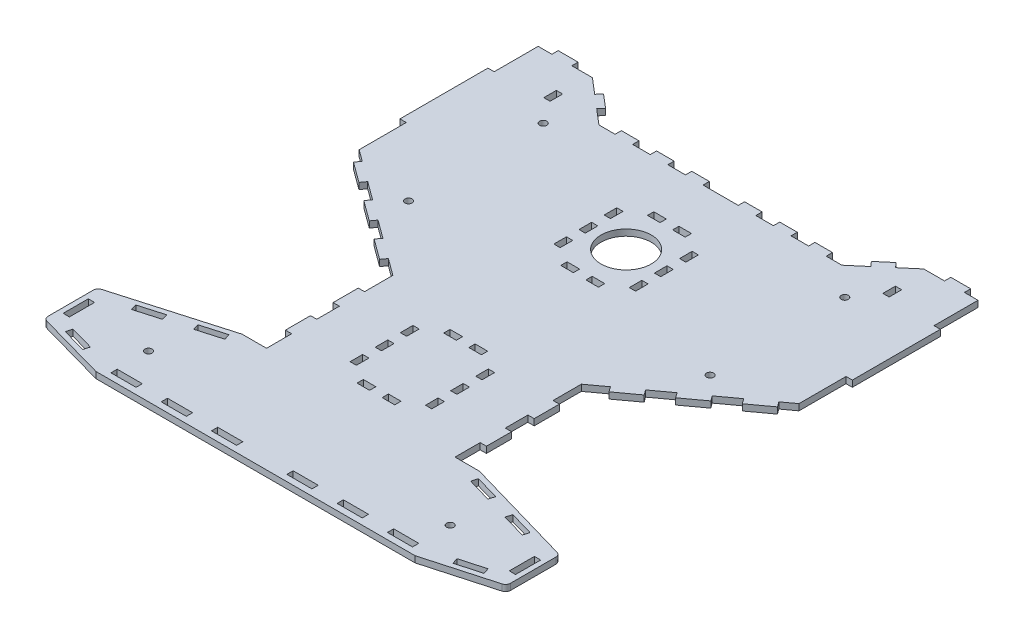
SolidWorks part; units mm, degrees
material "Beech"
ref_plane "Front" through (0, 0, 0) normal (0, 0, 1) x (1, 0, 0)
ref_plane "Top" through (0, 0, 0) normal (0, 1, 0) x (1, 0, 0)
ref_plane "Right" through (0, 0, 0) normal (1, 0, 0) x (0, 0, -1)
sketch "Sketch1" plane through (0, 0, 0) normal (0, 1, 0) x (1, 0, 0)
  line L0 (47.4037, 85) -> (-47.4037, 85) construction
  line L1 (-90, -100) -> (90, -100) construction
  line L2 (-90, -100) -> (-90, 100) construction
  line L3 (-90, 100) -> (90, 100) construction
  line L4 (90, -100) -> (90, 100) construction
  line L5 (-90, -100) -> (90, 100) construction
  line L6 (-90, 100) -> (90, -100) construction
  line L7 (-47.4037, 85) -> (-64.159, 99.2831) construction
  line L10 (-87.5, 23.171) -> (-40, -11.5806) construction
  line L14 (-90, -100) -> (90, -100) construction
  line L15 (0, 23.9102) -> (0, -23.5083) construction
  line L16 (90, -75) -> (90, -100) construction
  line L17 (40, -60.5806) -> (90, -75) construction
  line L18 (40, -11.5806) -> (40, -60.5806) construction
  line L22 (47.4037, 85) -> (64.159, 99.2831) construction
  line L23 (2.5, 63.5) -> (7.5, 63.5)
  line L30 (-15, 27.75) -> (15, 27.75) construction
  line L31 (-15, 27.75) -> (-15, 62.25) construction
  line L32 (-15, 62.25) -> (15, 62.25) construction
  line L33 (15, 27.75) -> (15, 62.25) construction
  line L34 (-15, 27.75) -> (15, 62.25) construction
  line L35 (-15, 62.25) -> (15, 27.75) construction
  line L36 (-7.5, 61) -> (-2.5, 61)
  line L37 (-7.5, 61) -> (-7.5, 63.5)
  line L38 (-7.5, 63.5) -> (-2.5, 63.5)
  line L39 (-2.5, 61) -> (-2.5, 63.5)
  line L40 (-7.5, 61) -> (-2.5, 63.5) construction
  line L41 (-7.5, 63.5) -> (-2.5, 61) construction
  line L42 (7.5, 61) -> (7.5, 63.5)
  line L43 (2.5, 61) -> (7.5, 61)
  line L44 (2.5, 61) -> (2.5, 63.5)
  line L53 (5.5621, 45) -> (-5.5621, 45) construction
  line L62 (-7.5, 26.5) -> (-2.5, 26.5)
  line L63 (-2.5, 29) -> (-2.5, 26.5)
  line L64 (-7.5, 29) -> (-2.5, 29)
  line L65 (-7.5, 29) -> (-7.5, 26.5)
  line L66 (2.5, 29) -> (2.5, 26.5)
  line L67 (2.5, 29) -> (7.5, 29)
  line L68 (7.5, 29) -> (7.5, 26.5)
  line L69 (2.5, 26.5) -> (7.5, 26.5)
  line L70 (-16.25, 47.5) -> (-16.25, 42.5)
  line L71 (-13.75, 57.5) -> (-16.25, 57.5)
  line L72 (-13.75, 57.5) -> (-13.75, 52.5)
  line L73 (-13.75, 52.5) -> (-16.25, 52.5)
  line L74 (-16.25, 57.5) -> (-16.25, 52.5)
  line L75 (-13.75, 57.5) -> (-16.25, 52.5) construction
  line L76 (-13.75, 52.5) -> (-16.25, 57.5) construction
  line L77 (-13.75, 42.5) -> (-16.25, 42.5)
  line L78 (-13.75, 47.5) -> (-13.75, 42.5)
  line L79 (-13.75, 47.5) -> (-16.25, 47.5)
  line L80 (-16.25, 37.5) -> (-16.25, 32.5)
  line L81 (-13.75, 32.5) -> (-16.25, 32.5)
  line L82 (-13.75, 37.5) -> (-13.75, 32.5)
  line L83 (-13.75, 37.5) -> (-16.25, 37.5)
  line L88 (13.75, 52.5) -> (16.25, 52.5)
  line L89 (16.25, 57.5) -> (16.25, 52.5)
  line L90 (13.75, 57.5) -> (16.25, 57.5)
  line L91 (13.75, 57.5) -> (13.75, 52.5)
  line L92 (13.75, 47.5) -> (16.25, 47.5)
  line L93 (13.75, 47.5) -> (13.75, 42.5)
  line L94 (13.75, 42.5) -> (16.25, 42.5)
  line L95 (16.25, 47.5) -> (16.25, 42.5)
  line L96 (13.75, 37.5) -> (16.25, 37.5)
  line L97 (13.75, 37.5) -> (13.75, 32.5)
  line L98 (13.75, 32.5) -> (16.25, 32.5)
  line L99 (16.25, 37.5) -> (16.25, 32.5)
  line L104 (-87.5, 80) -> (-90, 80)
  line L105 (87.5, 80) -> (90, 80)
  line L106 (87.5, 80) -> (87.5, 45)
  line L107 (87.5, 45) -> (90, 45)
  line L108 (90, 80) -> (90, 45)
  line L109 (87.5, 80) -> (90, 45) construction
  line L110 (87.5, 45) -> (90, 80) construction
  line L111 (-87.5, 80) -> (-87.5, 45)
  line L112 (-87.5, 45) -> (-90, 45)
  line L113 (-90, 80) -> (-90, 45)
  line L114 (-66.1052, 100) -> (-87.5, 100) construction
  line L115 (-87.5, 100) -> (-87.5, 23.171)
  line L116 (-87.5, 100.2764) -> (-87.5, 23.4474)
  line L117 (66.1052, 100) -> (87.5, 100) construction
  line L118 (87.5, 100) -> (87.5, 23.171)
  line L119 (-13.75, -28.5806) -> (-16.25, -28.5806)
  line L122 (-13.75, -23.5806) -> (-16.25, -28.5806) construction
  line L123 (-7.5, -20.0806) -> (-2.5, -17.5806) construction
  line L125 (-15, -18.8306) -> (15, -53.3306) construction
  line L129 (-13.75, -23.5806) -> (-13.75, -28.5806)
  line L130 (-13.75, -23.5806) -> (-16.25, -23.5806)
  line L134 (-15, -53.3306) -> (15, -18.8306) construction
  line L135 (-15, -53.3306) -> (-15, -18.8306) construction
  line L142 (-7.5, -17.5806) -> (-2.5, -20.0806) construction
  line L152 (-16.25, -23.5806) -> (-16.25, -28.5806)
  line L160 (-7.5, -20.0806) -> (-7.5, -17.5806)
  line L163 (15, -53.3306) -> (15, -18.8306) construction
  line L168 (-87.5, 97.5) -> (-62.0673, 97.5) construction
  line L174 (-15, -18.8306) -> (15, -18.8306) construction
  line L180 (-7.5, -20.0806) -> (-2.5, -20.0806)
  line L183 (-15, -53.3306) -> (15, -53.3306) construction
  line L184 (-2.5, -20.0806) -> (-2.5, -17.5806)
  line L185 (-7.5, -17.5806) -> (-2.5, -17.5806)
  line L193 (5.7531, -36.0806) -> (-5.3943, -36.0806) construction
  line L197 (-65.921, 97.5) -> (-48.3247, 82.5) construction
  line L199 (-13.75, -28.5806) -> (-16.25, -23.5806) construction
  line L200 (2.5, -20.0806) -> (2.5, -17.5806)
  line L201 (2.5, -17.5806) -> (7.5, -17.5806)
  line L202 (7.5, -20.0806) -> (7.5, -17.5806)
  line L203 (2.5, -20.0806) -> (7.5, -20.0806)
  line L212 (-13.75, -38.5806) -> (-16.25, -38.5806)
  line L213 (-16.25, -33.5806) -> (-16.25, -38.5806)
  line L214 (-13.75, -33.5806) -> (-16.25, -33.5806)
  line L215 (-13.75, -33.5806) -> (-13.75, -38.5806)
  line L216 (-13.75, -48.5806) -> (-16.25, -48.5806)
  line L217 (-16.25, -43.5806) -> (-16.25, -48.5806)
  line L218 (-13.75, -43.5806) -> (-16.25, -43.5806)
  line L219 (-13.75, -43.5806) -> (-13.75, -48.5806)
  line L232 (2.5, -52.0806) -> (7.5, -52.0806)
  line L233 (7.5, -52.0806) -> (7.5, -54.5806)
  line L234 (2.5, -54.5806) -> (7.5, -54.5806)
  line L235 (2.5, -52.0806) -> (2.5, -54.5806)
  line L236 (-7.5, -52.0806) -> (-2.5, -52.0806)
  line L237 (-2.5, -52.0806) -> (-2.5, -54.5806)
  line L238 (-7.5, -54.5806) -> (-2.5, -54.5806)
  line L239 (-7.5, -52.0806) -> (-7.5, -54.5806)
  line L240 (13.75, -23.5806) -> (13.75, -28.5806)
  line L241 (13.75, -23.5806) -> (16.25, -23.5806)
  line L242 (16.25, -23.5806) -> (16.25, -28.5806)
  line L243 (13.75, -28.5806) -> (16.25, -28.5806)
  line L244 (13.75, -33.5806) -> (13.75, -38.5806)
  line L245 (13.75, -33.5806) -> (16.25, -33.5806)
  line L246 (16.25, -33.5806) -> (16.25, -38.5806)
  line L247 (13.75, -38.5806) -> (16.25, -38.5806)
  line L248 (13.75, -43.5806) -> (13.75, -48.5806)
  line L249 (13.75, -43.5806) -> (16.25, -43.5806)
  line L250 (16.25, -43.5806) -> (16.25, -48.5806)
  line L251 (13.75, -48.5806) -> (16.25, -48.5806)
  line L256 (-16.25, 27.5) -> (-16.25, 22.5) [skipped]
  line L257 (-13.75, 22.5) -> (-16.25, 22.5) [skipped]
  line L258 (-13.75, 27.5) -> (-13.75, 22.5) [skipped]
  line L259 (-13.75, 27.5) -> (-16.25, 27.5) [skipped]
  line L260 (22.5, 63.5) -> (27.5, 63.5) [skipped]
  line L261 (27.5, 61) -> (27.5, 63.5) [skipped]
  line L262 (22.5, 61) -> (27.5, 61) [skipped]
  line L263 (22.5, 61) -> (22.5, 63.5) [skipped]
  line L264 (12.5, 63.5) -> (17.5, 63.5) [skipped]
  line L265 (17.5, 61) -> (17.5, 63.5) [skipped]
  line L266 (12.5, 61) -> (17.5, 61) [skipped]
  line L267 (12.5, 61) -> (12.5, 63.5) [skipped]
  line L268 (12.5, -20.0806) -> (12.5, -17.5806) [skipped]
  line L269 (12.5, -17.5806) -> (17.5, -17.5806) [skipped]
  line L270 (17.5, -20.0806) -> (17.5, -17.5806) [skipped]
  line L271 (12.5, -20.0806) -> (17.5, -20.0806) [skipped]
  line L272 (22.5, -20.0806) -> (22.5, -17.5806) [skipped]
  line L273 (22.5, -17.5806) -> (27.5, -17.5806) [skipped]
  line L274 (27.5, -20.0806) -> (27.5, -17.5806) [skipped]
  line L275 (22.5, -20.0806) -> (27.5, -20.0806) [skipped]
  line L276 (-13.75, -58.5806) -> (-16.25, -58.5806) [skipped]
  line L277 (-16.25, -53.5806) -> (-16.25, -58.5806) [skipped]
  line L278 (-13.75, -53.5806) -> (-16.25, -53.5806) [skipped]
  line L279 (-13.75, -53.5806) -> (-13.75, -58.5806) [skipped]
  line L280 (-48.3247, 82.5) -> (48.3247, 82.5) construction
  line L281 (48.3247, 82.5) -> (65.921, 97.5) construction
  line L282 (62.0673, 97.5) -> (87.5, 97.5) construction
  line L283 (87.5, 97.5) -> (82.1, 97.5)
  line L284 (82.1, 97.5) -> (82.1, 100)
  line L285 (82.1, 100) -> (74.1773, 100)
  line L286 (74.1773, 100) -> (74.1773, 97.5)
  line L287 (74.1773, 97.5) -> (65.921, 97.5)
  line L288 (65.921, 97.5) -> (59.8556, 92.3296)
  line L289 (59.8556, 92.3296) -> (58.2338, 94.2322)
  line L290 (58.2338, 94.2322) -> (52.9067, 89.691)
  line L291 (52.9067, 89.691) -> (54.5285, 87.7885)
  line L292 (54.5285, 87.7885) -> (48.3247, 82.5)
  line L293 (28.1, 85) -> (28.1, 82.5)
  line L294 (28.1, 82.5) -> (35.1, 82.5)
  line L295 (35.1, 82.5) -> (35.1, 85)
  line L296 (35.1, 85) -> (42.1, 85)
  line L297 (42.1, 85) -> (42.1, 82.5)
  line L298 (42.1, 82.5) -> (48.3247, 82.5)
  line L299 (28.1, 85) -> (21.1, 85)
  line L300 (21.1, 85) -> (21.1, 82.5)
  line L301 (21.1, 82.5) -> (14.1, 82.5)
  line L302 (14.1, 82.5) -> (14.1, 85)
  line L303 (14.1, 85) -> (7.1, 85)
  line L304 (7.1, 85) -> (7.1, 82.5)
  line L305 (7.1, 82.5) -> (-6.9, 82.5)
  line L306 (-6.9, 82.5) -> (-6.9, 85)
  line L307 (-6.9, 85) -> (-13.9, 85)
  line L308 (-13.9, 85) -> (-13.9, 82.5)
  line L309 (-13.9, 82.5) -> (-20.9, 82.5)
  line L310 (-20.9, 82.5) -> (-20.9, 85)
  line L311 (-20.9, 85) -> (-27.9, 85)
  line L312 (-27.9, 85) -> (-27.9, 82.5)
  line L313 (-27.9, 82.5) -> (-34.9, 82.5)
  line L314 (-34.9, 82.5) -> (-34.9, 85)
  line L315 (-34.9, 85) -> (-41.9, 85)
  line L316 (-41.9, 85) -> (-41.9, 82.5)
  line L317 (-41.9, 82.5) -> (-48.3247, 82.5)
  line L318 (-48.3247, 82.5) -> (-54.3915, 87.6717)
  line L319 (-54.3915, 87.6717) -> (-52.7697, 89.5743)
  line L320 (-52.7697, 89.5743) -> (-58.0968, 94.1154)
  line L321 (-58.0968, 94.1154) -> (-59.7187, 92.2128)
  line L322 (-59.7187, 92.2128) -> (-65.921, 97.5)
  line L323 (-65.921, 97.5) -> (-74.1173, 97.5)
  line L324 (-74.1173, 97.5) -> (-74.1173, 100)
  line L325 (-74.1173, 100) -> (-82.04, 100)
  line L326 (-82.04, 100) -> (-82.04, 97.5)
  line L327 (-82.04, 97.5) -> (-87.5, 97.5)
  line L328 (-87.5, 26.2686) -> (-37.5, -10.312) construction
  line L329 (-40, -11.5806) -> (-37.5, -11.5806) construction
  line L330 (-38.5238, -9.563) -> (-44.1733, -5.4298)
  line L331 (-44.1733, -5.4298) -> (-45.6495, -7.4474)
  line L332 (-45.6495, -7.4474) -> (-53.7201, -1.5428)
  line L333 (-53.7201, -1.5428) -> (-52.244, 0.4749)
  line L334 (-52.244, 0.4749) -> (-59.4874, 5.7742)
  line L335 (-59.4874, 5.7742) -> (-60.9636, 3.7566)
  line L336 (-60.9636, 3.7566) -> (-69.0342, 9.6612)
  line L337 (-69.0342, 9.6612) -> (-67.5581, 11.6788)
  line L338 (-67.5581, 11.6788) -> (-74.8015, 16.9782)
  line L339 (-74.8015, 16.9782) -> (-76.2776, 14.9606)
  line L340 (-76.2776, 14.9606) -> (-84.3483, 20.8652)
  line L341 (-84.3483, 20.8652) -> (-82.8722, 22.8828)
  line L342 (-82.8722, 22.8828) -> (-87.5, 26.2686)
  line L343 (87.5, 26.2686) -> (37.5, -10.312) construction
  line L344 (87.5, 23.171) -> (40, -11.5806) construction
  line L345 (82.8722, 22.8828) -> (87.5, 26.2686)
  line L346 (84.3483, 20.8652) -> (82.8722, 22.8828)
  line L347 (76.2776, 14.9606) -> (84.3483, 20.8652)
  line L348 (74.8015, 16.9782) -> (76.2776, 14.9606)
  line L349 (67.5581, 11.6788) -> (74.8015, 16.9782)
  line L350 (69.0342, 9.6612) -> (67.5581, 11.6788)
  line L351 (60.9636, 3.7566) -> (69.0342, 9.6612)
  line L352 (59.4874, 5.7742) -> (60.9636, 3.7566)
  line L353 (52.244, 0.4749) -> (59.4874, 5.7742)
  line L354 (53.7201, -1.5428) -> (52.244, 0.4749)
  line L355 (45.6495, -7.4474) -> (53.7201, -1.5428)
  line L356 (44.1733, -5.4298) -> (45.6495, -7.4474)
  line L357 (38.5238, -9.563) -> (44.1733, -5.4298)
  line L358 (40, -11.5806) -> (38.5238, -9.563) construction
  line L359 (37.5, -10.312) -> (37.5, -60.5806) construction
  line L360 (37.5, -60.5806) -> (40, -60.5806) construction
  line L361 (38.5238, -9.563) -> (37.5, -10.312)
  line L362 (40, -11.5806) -> (37.5, -11.5806) construction
  line L363 (37.5, -10.312) -> (37.5, -11.5806)
  line L364 (37.5, -11.5806) -> (37.5, -21.5806)
  line L365 (37.5, -21.5806) -> (40, -21.5806)
  line L366 (40, -21.5806) -> (40, -31.5806)
  line L367 (40, -31.5806) -> (37.5, -31.5806)
  line L368 (37.5, -31.5806) -> (37.5, -40.5806)
  line L369 (37.5, -40.5806) -> (40, -40.5806)
  line L370 (40, -40.5806) -> (40, -50.5806)
  line L371 (40, -50.5806) -> (37.5, -50.5806)
  line L372 (37.5, -50.5806) -> (37.5, -60.5806)
  line L373 (-37.5, -10.312) -> (-37.5, -60.5806) construction
  line L374 (-40, -11.5806) -> (-38.5238, -9.563) construction
  line L375 (-40, -11.5806) -> (-40, -60.5806) construction
  line L376 (-37.5, -50.5806) -> (-37.5, -62.4616)
  line L377 (-40, -50.5806) -> (-37.5, -50.5806)
  line L378 (-40, -40.5806) -> (-40, -50.5806)
  line L379 (-37.5, -40.5806) -> (-40, -40.5806)
  line L380 (-37.5, -31.5806) -> (-37.5, -40.5806)
  line L381 (-40, -31.5806) -> (-37.5, -31.5806)
  line L382 (-40, -21.5806) -> (-40, -31.5806)
  line L383 (-37.5, -21.5806) -> (-40, -21.5806)
  line L384 (-37.5, -11.5806) -> (-37.5, -21.5806)
  line L385 (-37.5, -10.312) -> (-37.5, -11.5806)
  line L386 (-38.5238, -9.563) -> (-37.5, -10.312)
  line L387 (-37.5, -60.5806) -> (-40, -60.5806) construction
  line L388 (37.5, -62.4616) -> (87.5, -76.8809) construction
  line L389 (87.5, -76.8809) -> (87.5, -91.1038) construction
  line L390 (87.5, -91.1038) -> (64.6566, -97.5) construction
  line L391 (64.6566, -97.5) -> (-64.6566, -97.5) construction
  line L392 (90, -93) -> (65, -100) construction
  line L393 (37.5, -60.5806) -> (40, -60.5806)
  line L394 (40, -60.5806) -> (47.2177, -60.5806)
  line L395 (47.2177, -60.5806) -> (92, -73.4953)
  line L396 (40, -60.5806) -> (47.2177, -60.5806)
  line L401 (49.6084, -63.3516) -> (48.9157, -65.7537)
  line L402 (49.6084, -63.3516) -> (59.2169, -66.1225)
  line L403 (48.9157, -65.7537) -> (58.5241, -68.5246)
  line L404 (59.2169, -66.1225) -> (58.5241, -68.5246)
  line L405 (53.7199, -67.1392) -> (54.4126, -64.7371) construction
  line L406 (49.2621, -64.5526) -> (58.8705, -67.3236) construction
  line L407 (68.8253, -68.8935) -> (68.1325, -71.2956)
  line L408 (68.8253, -68.8935) -> (78.4337, -71.6644)
  line L409 (78.4337, -71.6644) -> (77.741, -74.0665)
  line L410 (68.1325, -71.2956) -> (77.741, -74.0665)
  line L411 (90, -89) -> (87.5, -89)
  line L412 (90, -89) -> (90, -79)
  line L413 (90, -79) -> (87.5, -79)
  line L414 (92, -73.4953) -> (92, -94.5169)
  line L415 (87.5, -89) -> (87.5, -79)
  line L416 (92, -94.5169) -> (63.489, -102.5)
  line L417 (72.9555, -95.1763) -> (73.6296, -97.5837)
  line L418 (63.489, -102.5) -> (-63.489, -102.5)
  line L419 (72.9555, -95.1763) -> (82.5852, -92.48)
  line L420 (82.5852, -92.48) -> (83.2593, -94.8874)
  line L421 (73.6296, -97.5837) -> (83.2593, -94.8874)
  line L422 (50, -97.5) -> (50, -100)
  line L423 (50, -97.5) -> (60, -97.5)
  line L424 (60, -97.5) -> (60, -100)
  line L425 (50, -100) -> (60, -100)
  line L426 (30, -97.5) -> (30, -100)
  line L427 (30, -100) -> (40, -100)
  line L428 (40, -97.5) -> (40, -100)
  line L429 (30, -97.5) -> (40, -97.5)
  line L430 (10, -97.5) -> (10, -100)
  line L431 (10, -100) -> (20, -100)
  line L432 (20, -97.5) -> (20, -100)
  line L433 (10, -97.5) -> (20, -97.5)
  line L434 (-49.2621, -64.5526) -> (-58.8705, -67.3236) construction
  line L435 (-53.7199, -67.1392) -> (-54.4126, -64.7371) construction
  line L436 (-90, -93) -> (-65, -100) construction
  line L437 (-87.5, -91.1038) -> (-64.6566, -97.5) construction
  line L438 (-87.5, -76.8809) -> (-87.5, -91.1038) construction
  line L439 (-37.5, -62.4616) -> (-87.5, -76.8809) construction
  line L440 (-40, -60.5806) -> (-90, -75) construction
  line L441 (-10, -97.5) -> (-20, -97.5)
  line L442 (-20, -97.5) -> (-20, -100)
  line L443 (-10, -100) -> (-20, -100)
  line L444 (-10, -97.5) -> (-10, -100)
  line L445 (-30, -97.5) -> (-40, -97.5)
  line L446 (-40, -97.5) -> (-40, -100)
  line L447 (-30, -100) -> (-40, -100)
  line L448 (-30, -97.5) -> (-30, -100)
  line L449 (-50, -100) -> (-60, -100)
  line L450 (-60, -97.5) -> (-60, -100)
  line L451 (-50, -97.5) -> (-60, -97.5)
  line L452 (-50, -97.5) -> (-50, -100)
  line L453 (-73.6296, -97.5837) -> (-83.2593, -94.8874)
  line L454 (-82.5852, -92.48) -> (-83.2593, -94.8874)
  line L455 (-72.9555, -95.1763) -> (-82.5852, -92.48)
  line L456 (-72.9555, -95.1763) -> (-73.6296, -97.5837)
  line L457 (-92, -94.5169) -> (-63.489, -102.5)
  line L458 (-87.5, -89) -> (-87.5, -79)
  line L459 (-92, -73.4953) -> (-92, -94.5169)
  line L460 (-90, -79) -> (-87.5, -79)
  line L461 (-90, -89) -> (-90, -79)
  line L462 (-90, -89) -> (-87.5, -89)
  line L463 (-68.1325, -71.2956) -> (-77.741, -74.0665)
  line L464 (-78.4337, -71.6644) -> (-77.741, -74.0665)
  line L465 (-68.8253, -68.8935) -> (-78.4337, -71.6644)
  line L466 (-68.8253, -68.8935) -> (-68.1325, -71.2956)
  line L467 (-59.2169, -66.1225) -> (-58.5241, -68.5246)
  line L468 (-48.9157, -65.7537) -> (-58.5241, -68.5246)
  line L469 (-49.6084, -63.3516) -> (-59.2169, -66.1225)
  line L470 (-49.6084, -63.3516) -> (-48.9157, -65.7537)
  line L471 (-40, -60.5806) -> (-47.2177, -60.5806)
  line L472 (-47.2177, -60.5806) -> (-92, -73.4953)
  line L473 (-40, -60.5806) -> (-47.2177, -60.5806)
  line L474 (-40, -60.5806) -> (-37.5, -60.5806)
  line L475 (-66.2, 85.93) -> (-68.7, 85.93)
  line L476 (66.2, 80.93) -> (68.7, 80.93)
  line L477 (66.2, 80.93) -> (66.2, 85.93)
  line L478 (66.2, 85.93) -> (68.7, 85.93)
  line L479 (68.7, 80.93) -> (68.7, 85.93)
  line L480 (66.2, 80.93) -> (68.7, 85.93) construction
  line L481 (66.2, 85.93) -> (68.7, 80.93) construction
  line L482 (-68.7, 80.93) -> (-68.7, 85.93)
  line L483 (-66.2, 80.93) -> (-68.7, 80.93)
  line L484 (-66.2, 80.93) -> (-66.2, 85.93)
  circle A4 centre (-60, 72) radius 1.425
  circle A9 centre (60, 72) radius 1.425
  arc A12 (-64.159, 99.2831) -> (-66.1052, 100) centre (-66.1052, 97) ccw construction
  arc A13 (66.1052, 100) -> (64.159, 99.2831) centre (66.1052, 97) ccw construction
  circle A14 centre (0, 45) radius 10
  circle A15 centre (-60, -85) radius 1.425
  circle A16 centre (60, -85) radius 1.425
  circle A17 centre (-60, 18.4194) radius 1.425
  circle A18 centre (60, 18.4194) radius 1.425
  point P0 (0, 0)
  point P16 (0, -100)
  point P22 (0, 85)
  point P24 (0, -36.0806)
  point P28 (-87.5, 62.5)
  point P34 (0, 45)
  point P42 (0, 0)
  point P48 (90, -75)
  point P61 (88.75, 62.5)
  point P66 (87.5, 23.171)
  point P70 (0, 45)
  point P76 (-5, 62.25)
  point P112 (-15, 57.5)
  point P113 (-15, 55)
  point P150 (-5, -18.8306)
  point P157 (0, -36.0806)
  point P187 (-15, -26.0806)
  point P221 (40, -36.0806)
  point P223 (-5, -20.0806)
  point P345 (0, -102.5)
  point P359 (0, -97.5926)
  point P388 (-54.0663, -65.9381)
  point P393 (67.45, 83.43)
  point P399 (-38.75, -11.5806)
  point P502 (54.0663, -65.9381)
  dimension "D12" = 37.5
  dimension "D14" = 2.85
  dimension "D15" = 18
  dimension "D16" = 20
  dimension "D30" = 40
  dimension "D13" = 94.8074
  dimension "D1" = 200
  dimension "D3" = 25
  dimension "D4" = 4.75
  dimension "D5" = 49
  dimension "D7" = 11.5806
  dimension "D8" = 15
  dimension "D9" = 2.5
  dimension "D10" = 52.5
  dimension "D11" = 2.5
  dimension "D17" = 30
  dimension "D18" = 34.5
  dimension "D19" = 30
  dimension "D20" = 2.5
  dimension "D21" = 5
  dimension "D22" = 7.5
  dimension "D23" = 4
  dimension "D24" = 5
  dimension "D25" = 2.5
  dimension "D26" = 5
  dimension "D27" = 4.75
  dimension "D29" = 5
  dimension "D31" = 21.3948
  dimension "D32" = 35
  dimension "D33" = 2.5
  dimension "D34" = 7.5
  dimension "D37" = 5
  dimension "D38" = 2.5
  dimension "D39" = 5
  dimension "D40" = 2.5
  dimension "D41" = 5
  dimension "D42" = 5
  dimension "D43" = 2.5
  dimension "D44" = 2.5
  dimension "D45" = 2.5
  dimension "D46" = 2.5
  dimension "D47" = 7
  dimension "D48" = 14
  dimension "D49" = 5.46
  dimension "D50" = 12.05
  dimension "D51" = 7.97
  dimension "D52" = 7
  dimension "D53" = 8.15
  dimension "D54" = 6.4247
  dimension "D55" = 5.4
  dimension "D56" = 2.5
  dimension "D57" = 7
  dimension "D58" = 10
  dimension "D59" = 8.975
  dimension "D60" = 10
  dimension "D61" = 76.829
  dimension "D62" = 25
  dimension "D63" = 2.5
  dimension "D64" = 2.5
  dimension "D65" = 2.5
  dimension "D66" = 180
  dimension "D67" = 2
  dimension "D68" = 2
  dimension "D69" = 2
  dimension "D70" = 2.5
  dimension "D71" = 2.5
  dimension "D72" = 10
  dimension "D73" = 10
  dimension "D75" = 10
  dimension "D76" = 4
  dimension "D77" = 7
  dimension "D78" = 5
  dimension "D80" = 10
  dimension "D81" = 16.57
  dimension "D82" = 21.3
  dimension "D83" = 5
  dimension "D84" = 28
  dimension "D85" = 8.1963
  dimension "D86" = 30
  dimension "D87" = 30
  dimension "D88" = 30
  dimension "D28" = 4
  dimension "D35" = 4
  dimension "D36" = 4
  dimension "D74" = 2
  dimension "D79" = 3
extrude "Boss-Extrude1" add sketch "Sketch1" along normal blind 2.5
fillet "Fillet2" radius 2 4 edges at (92, 1.25, 94.5169) (92, 1.25, 73.4953) (-92, 1.25, 94.5169) (-92, 1.25, 73.4953)
